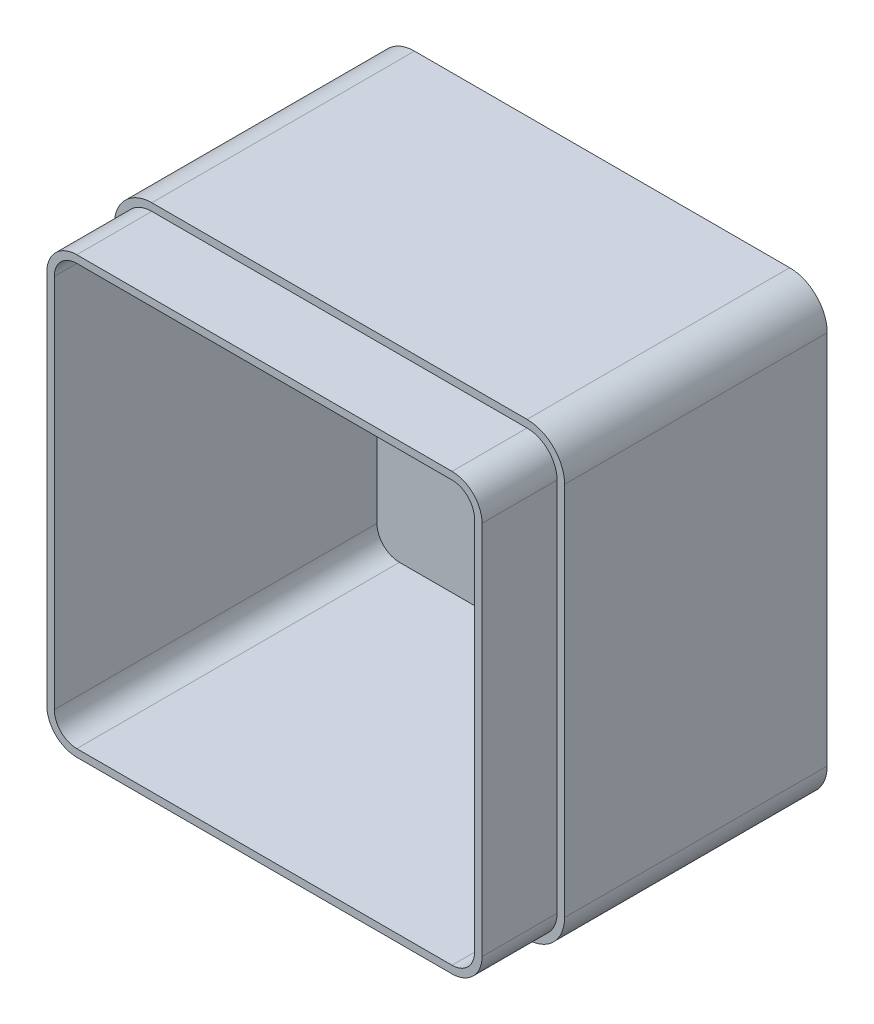
SolidWorks part; units mm, degrees
ref_plane "Plan de face" through (0, 0, 0) normal (0, 0, 1) x (1, 0, 0)
ref_plane "Plan de dessus" through (0, 0, 0) normal (0, 1, 0) x (1, 0, 0)
ref_plane "Plan de droite" through (0, 0, 0) normal (1, 0, 0) x (0, 0, -1)
sketch "Esquisse1" plane through (0, 0, 0) normal (0, 0, 1) x (1, 0, 0)
  line L1 (0, 0) -> (120, 0)
  line L2 (0, 0) -> (0, 120)
  line L3 (0, 120) -> (120, 120)
  line L4 (120, 0) -> (120, 120)
  dimension "D1" = 120
  dimension "D2" = 120
extrude "Boss.-Extru.1" add sketch "Esquisse1" along normal blind 90 contours L2 L1 L4 L3
fillet "Congé1" radius 10 4 edges at (120, 0, 45) (0, 0, 45) (120, 120, 45) (0, 120, 45)
shell "Coque5" thickness 4
sketch "Esquisse11" plane through (0, 0, 90) normal (0, 0, 1) x (1, 0, 0)
  line L0 (110, 118) -> (10, 118)
  line L1 (2, 110) -> (2, 10)
  line L2 (10, 2) -> (110, 2)
  line L3 (118, 10) -> (118, 110)
  line L4 (10, 0) -> (110, 0)
  line L5 (120, 10) -> (120, 110)
  line L6 (110, 120) -> (10, 120)
  line L7 (0, 110) -> (0, 10)
  line L8 (10, 0) -> (110, 0)
  line L9 (120, 10) -> (120, 110)
  line L10 (110, 120) -> (10, 120)
  line L11 (0, 110) -> (0, 10)
  arc A0 (10, 118) -> (2, 110) centre (10, 110) ccw
  arc A1 (2, 10) -> (10, 2) centre (10, 10) ccw
  arc A2 (110, 2) -> (118, 10) centre (110, 10) ccw
  arc A3 (118, 110) -> (110, 118) centre (110, 110) ccw
  arc A4 (110, 0) -> (120, 10) centre (110, 10) ccw
  arc A5 (120, 110) -> (110, 120) centre (110, 110) ccw
  arc A6 (10, 120) -> (0, 110) centre (10, 110) ccw
  arc A7 (0, 10) -> (10, 0) centre (10, 10) ccw
  arc A8 (110, 0) -> (120, 10) centre (110, 10) ccw
  arc A9 (120, 110) -> (110, 120) centre (110, 110) ccw
  arc A10 (10, 120) -> (0, 110) centre (10, 110) ccw
  arc A11 (0, 10) -> (10, 0) centre (10, 10) ccw
  dimension "D1" = 0
  dimension "D2" = 2
extrude "Enlèv. mat.-Extru.2" cut sketch "Esquisse11" against normal blind 20
